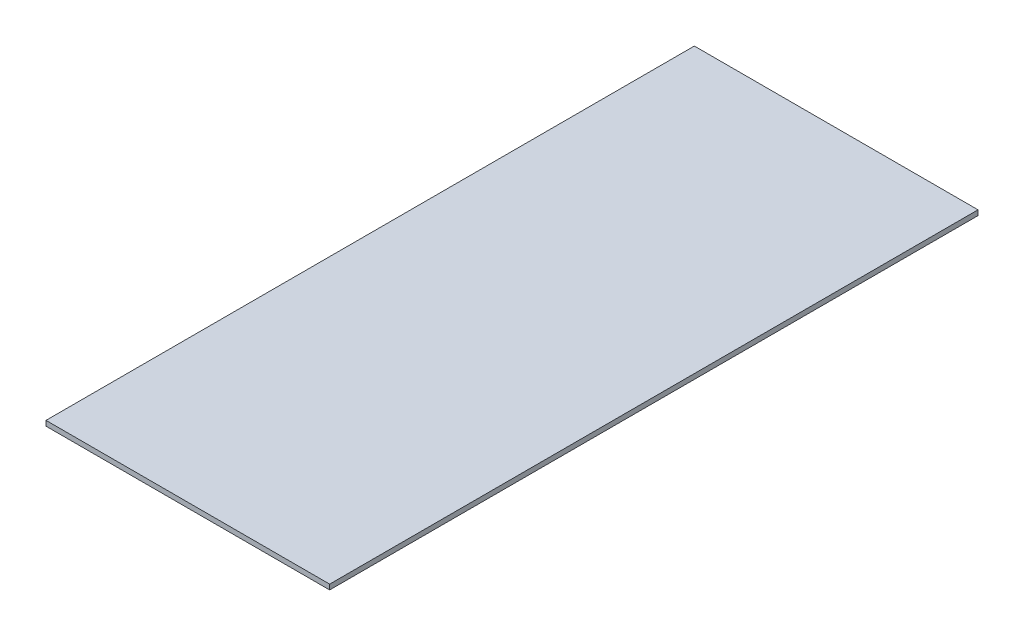
SolidWorks part; units mm, degrees
material "Acrylic (Medium-high impact)"
ref_plane "Front Plane" through (0, 0, 0) normal (0, 0, 1) x (1, 0, 0)
ref_plane "Top Plane" through (0, 0, 0) normal (0, 1, 0) x (1, 0, 0)
ref_plane "Right Plane" through (0, 0, 0) normal (1, 0, 0) x (0, 0, -1)
sketch "Sketch1" plane through (0, 0, 0) normal (0, 1, 0) x (1, 0, 0)
  line L0 (0, -1.7463) -> (0, 1.7463) construction
  line L1 (-88.9, -203.2) -> (88.9, -203.2)
  line L2 (-88.9, -203.2) -> (-88.9, 203.2)
  line L3 (-88.9, 203.2) -> (88.9, 203.2)
  line L4 (88.9, -203.2) -> (88.9, 203.2)
  line L5 (-88.9, -203.2) -> (88.9, 203.2) construction
  line L6 (-88.9, 203.2) -> (88.9, -203.2) construction
  point P0 (0, 0)
  dimension "D1" = 177.8
  dimension "D2" = 406.4
extrude "Boss-Extrude1" add sketch "Sketch1" along normal blind 3.175
sketch "Sketch2" [suppressed] plane through (0, 0, 0) normal (0, 1, 0) x (1, 0, 0)
  line L1 (-163.5125, -61.9125) -> (87.3125, -61.9125)
  line L2 (-163.5125, -61.9125) -> (-163.5125, -120.6136)
  line L3 (-163.5125, -120.6136) -> (87.3125, -120.6136)
  line L4 (87.3125, -61.9125) -> (87.3125, -120.6136)
  line L5 (163.5125, -61.9125) -> (163.5125, 61.9125) construction
  dimension "D1" = 76.2
  dimension "D2" = 58.7011
extrude "Boss-Extrude2" [suppressed] add sketch "Sketch2" along normal blind 3.175 contours L2 L3 L4 L1
